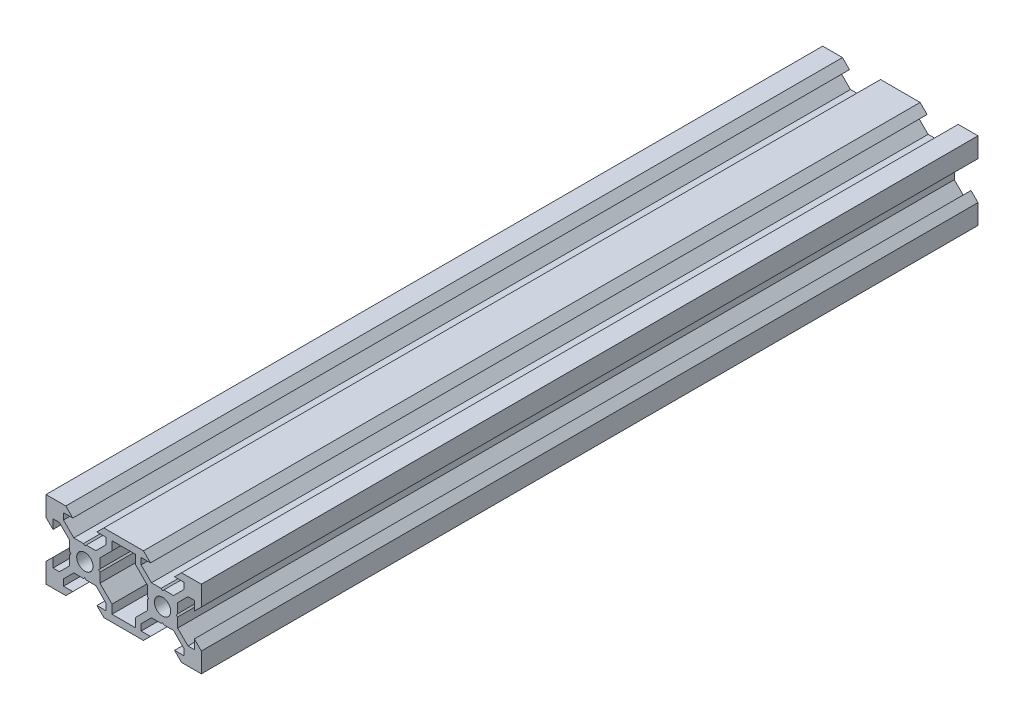
SolidWorks part; units mm, degrees
ref_plane "前视基准面" through (0, 0, 0) normal (0, 0, 1) x (1, 0, 0)
ref_plane "上视基准面" through (0, 0, 0) normal (0, 1, 0) x (1, 0, 0)
ref_plane "右视基准面" through (0, 0, 0) normal (1, 0, 0) x (0, 0, -1)
sketch "草图1" plane through (0, 0, 0) normal (0, 0, 1) x (1, 0, 0)
  line L1 (-20, 10) -> (20, 10)
  line L2 (-20, 10) -> (-20, -10)
  line L3 (-20, -10) -> (20, -10)
  line L4 (20, 10) -> (20, -10)
  line L5 (-20, 10) -> (20, -10) construction
  line L6 (-20, -10) -> (20, 10) construction
  point P0 (0, 0)
  dimension "D1" = 20
  dimension "D2" = 40
extrude "凸台-拉伸1" add sketch "草图1" against normal blind 200
sketch "草图2" plane through (0, 0, 0) normal (0, 0, 1) x (1, 0, 0)
  line L0 (0, -1000) -> (0, 49000) construction
  circle A0 centre (-10, 0) radius 2.1
  circle A1 centre (10, 0) radius 2.1
  dimension "D1" = 4.2
  dimension "D2" = 10
extrude "切除-拉伸1" cut sketch "草图2" against normal through all
sketch "草图3" plane through (0, 0, 0) normal (0, 0, 1) x (1, 0, 0)
  line L0 (10, 0) -> (35365.3391, 35355.3391) construction
  line L1 (10, 0) -> (35365.3391, -35355.3391) construction
  line L2 (16.56, 5.4993) -> (13.9007, 2.84)
  line L3 (13.9007, 2.84) -> (13.9007, 0.3536)
  line L4 (13.9007, -2.84) -> (16.56, -5.4993)
  line L5 (16.56, 5.4993) -> (18.2, 5.4993)
  line L6 (18.2, 5.4993) -> (18.2, 3.1)
  line L7 (18.2, -5.4993) -> (16.56, -5.4993)
  line L8 (-1000, 0) -> (49000, 0) construction
  line L9 (20, -10) -> (20, 10) construction
  line L10 (18.2, 3.1) -> (20, 4.9)
  line L11 (18.2, -3.1) -> (20, -4.9)
  line L12 (20, 4.9) -> (20, -4.9)
  line L13 (18.2, -3.1) -> (18.2, -5.4993)
  line L14 (13.9007, 0.3536) -> (13.5471, 0)
  line L15 (13.5471, 0) -> (13.9007, -0.3536)
  line L16 (13.9007, -0.3536) -> (13.9007, -2.84)
  point P18 (18.2, 3.1)
  point P20 (18.2, -3.1)
  dimension "D1" = 5.68
  dimension "D2" = 1.8
  dimension "D3" = 1.5
  dimension "D4" = 1.64
  dimension "D5" = 6.2
  dimension "D6" = 0.5
extrude "切除-拉伸2" cut sketch "草图3" against normal through all
pattern_circular "阵列(圆周)1" count 4 over 360 about axis through (10, 0, 0) along (0, 0, 1) of "切除-拉伸2"
mirror "镜向1" about plane through (0, 0, 0) normal (1, 0, 0) of "阵列(圆周)1", "切除-拉伸2"
sketch "草图4" plane through (0, 0, 0) normal (0, 0, 1) x (1, 0, 0)
  line L0 (-6.9, 8.2) -> (-4.5007, 8.2) construction
  line L1 (-3.0007, -8.2) -> (3.0007, -8.2)
  line L2 (-3.0007, -8.2) -> (-3.0007, -5.9387)
  line L3 (-3.0007, 8.2) -> (3.0007, 8.2)
  line L4 (3.0007, -8.2) -> (3.0007, -5.9387)
  line L5 (-3.0007, -8.2) -> (3.0007, 8.2) construction
  line L6 (-3.0007, 8.2) -> (3.0007, -8.2) construction
  line L8 (-6.0993, 2.84) -> (-3.0007, 5.9387)
  line L9 (-6.0993, 2.84) -> (-6.0993, -2.84)
  line L10 (-6.0993, -2.84) -> (-3.0007, -5.9387)
  line L11 (6.0993, 2.84) -> (3.0007, 5.9387)
  line L12 (6.0993, 2.84) -> (6.0993, -2.84)
  line L13 (6.0993, -2.84) -> (3.0007, -5.9387)
  line L15 (-6.0993, 2.84) -> (-3.44, 5.4993) construction
  line L16 (-3.44, -5.4993) -> (-6.0993, -2.84) construction
  line L17 (6.0993, 2.84) -> (3.44, 5.4993) construction
  line L18 (3.44, -5.4993) -> (6.0993, -2.84) construction
  line L19 (-3.0007, 5.9387) -> (-3.0007, 8.2)
  line L20 (3.0007, 5.9387) -> (3.0007, 8.2)
  line L21 (-4.5007, 8.2) -> (-4.5007, 6.56) construction
  point P0 (0, 0)
  point P30 (-4.5007, 7.38)
  dimension "D1" = 1.5
extrude "切除-拉伸3" cut sketch "草图4" against normal through all
